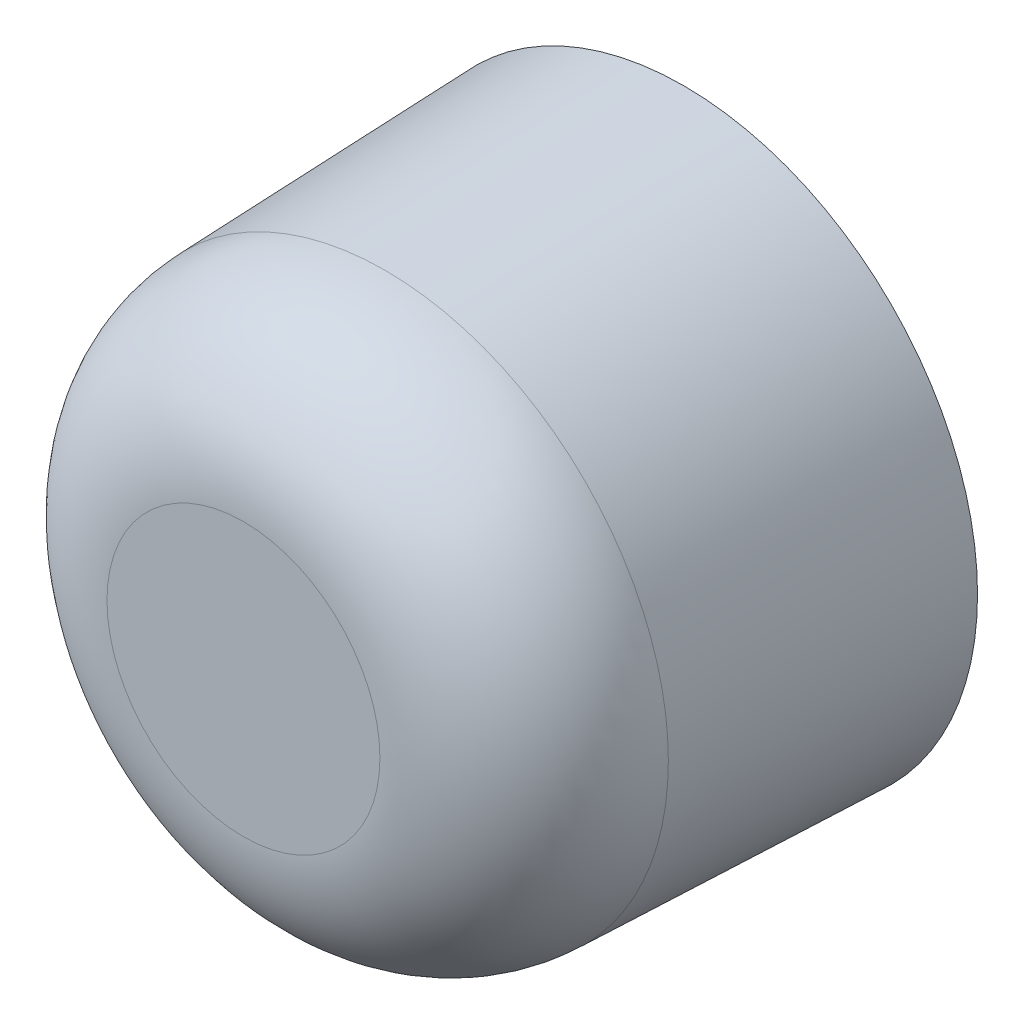
SolidWorks part; units mm, degrees
material "Plastique personnalisé"
ref_plane "Plan de face" through (0, 0, 0) normal (0, 0, 1) x (1, 0, 0)
ref_plane "Plan de dessus" through (0, 0, 0) normal (0, 1, 0) x (1, 0, 0)
ref_plane "Plan de droite" through (0, 0, 0) normal (1, 0, 0) x (0, 0, -1)
sketch "Esquisse1" plane through (0, 0, 0) normal (0, 0, 1) x (1, 0, 0)
  circle A0 centre (0, 0) radius 10
  dimension "D1" = 20
extrude "Boss.-Extru.1" add sketch "Esquisse1" along normal blind 15 draft 2
fillet "Congé1" radius 5 1 edges at (9.4762, 0, 15)
sketch "Esquisse2" plane through (0, 0, 0) normal (0, 0, -1) x (-1, 0, 0)
  circle A0 centre (0, 0) radius 3
extrude "Enlèv. mat.-Extru.1" cut sketch "Esquisse2" against normal blind 12
sketch "Esquisse3" plane through (0, 0, 0) normal (0, 0, -1) x (-1, 0, 0)
  circle A0 centre (0, 0) radius 7.5
  dimension "D1" = 15
extrude "Enlèv. mat.-Extru.2" cut sketch "Esquisse3" against normal blind 5
